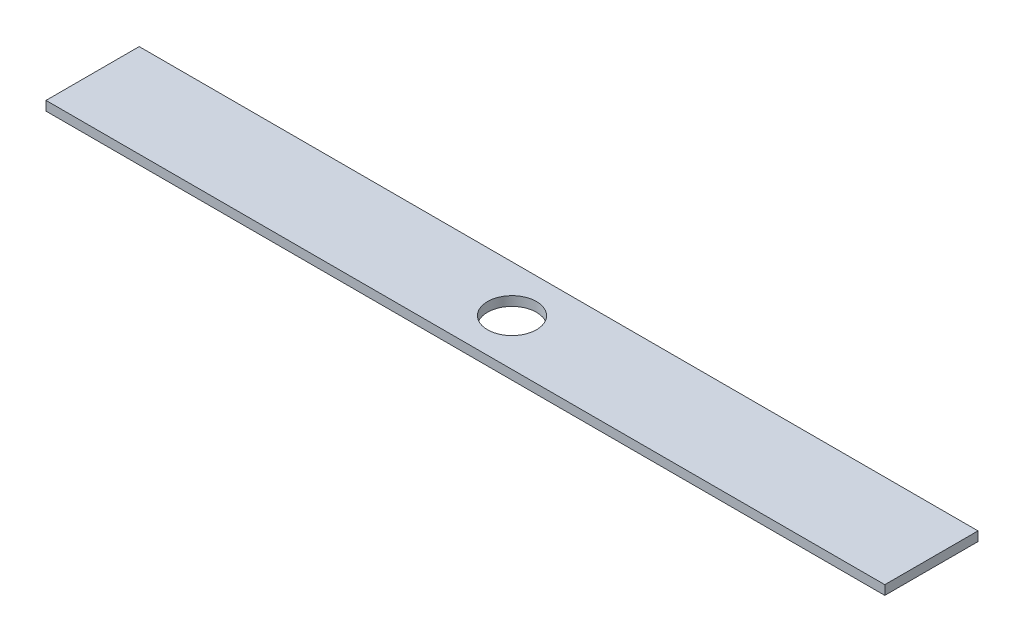
SolidWorks part; units mm, degrees
ref_plane "Front" through (0, 0, 0) normal (0, 0, 1) x (1, 0, 0)
ref_plane "Top" through (0, 0, 0) normal (0, 1, 0) x (1, 0, 0)
ref_plane "Right" through (0, 0, 0) normal (1, 0, 0) x (0, 0, -1)
sketch "Sketch1" plane through (0, 0, 0) normal (0, 1, 0) x (1, 0, 0)
  line L1 (90, 10) -> (-90, 10)
  line L2 (90, 10) -> (90, -10)
  line L3 (90, -10) -> (-90, -10)
  line L4 (-90, 10) -> (-90, -10)
  line L5 (90, 10) -> (-90, -10) construction
  line L6 (90, -10) -> (-90, 10) construction
  circle A0 centre (0, 0) radius 5.25
  point P0 (0, 0)
  dimension "D3" = 10.5
  dimension "D1" = 20
  dimension "D2" = 180
extrude "Boss-Extrude1" add sketch "Sketch1" along normal mid plane 2
